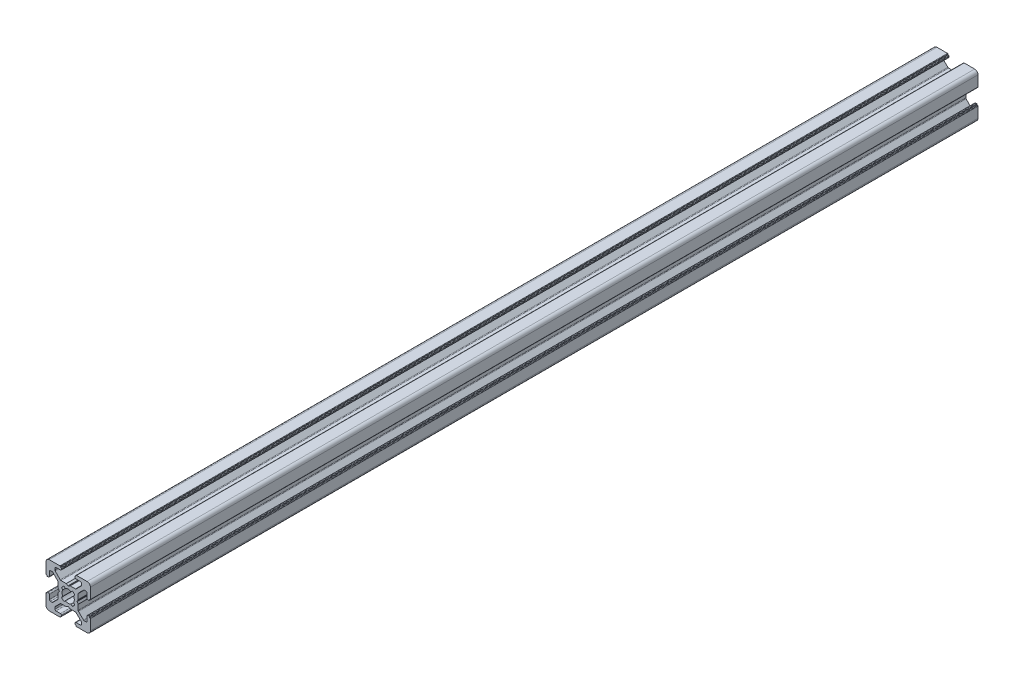
SolidWorks part; units mm, degrees
ref_plane "Front Plane" through (0, 0, 0) normal (0, 0, 1) x (1, 0, 0)
ref_plane "Top Plane" through (0, 0, 0) normal (0, 1, 0) x (1, 0, 0)
ref_plane "Right Plane" through (0, 0, 0) normal (1, 0, 0) x (0, 0, -1)
sketch "Sketch1" plane through (0, 0, 0) normal (0, 0, 1) x (1, 0, 0)
  line L0 (0, 13.3675) -> (0, -10.9159) construction
  line L1 (-12.9725, 0) -> (15.1887, 0) construction
  line L2 (-3.5, 8.5) -> (-5.5, 8.5)
  line L3 (-3.55, 9.7) -> (-3.55, 9.8)
  line L4 (-6, 7.2678) -> (-6, 8)
  line L5 (-7.2678, 6) -> (-8, 6)
  line L6 (-3.75, 10) -> (-8.5, 10)
  line L7 (-9.7, 3.55) -> (-9.8, 3.55)
  line L8 (-9.5, 3.2) -> (-9.5, 3.35)
  line L9 (-9, 3) -> (-9.3, 3)
  line L10 (-4.4732, 0.8536) -> (-4.0381, 0.1)
  line L11 (-4.5, 3.2322) -> (-4.5, 0.9536)
  line L12 (-8.5, 3.5) -> (-8.5, 5.5)
  line L13 (-10, 3.75) -> (-10, 8.5)
  line L14 (-3.5858, 4.6464) -> (-5.8536, 6.9142)
  line L15 (-4.6464, 3.5858) -> (-6.9142, 5.8536)
  line L16 (-3.2, 9.5) -> (-3.35, 9.5)
  line L17 (-3, 9) -> (-3, 9.3)
  line L18 (-0.8536, 4.4732) -> (-0.1, 4.0381)
  line L19 (-3.2322, 4.5) -> (-0.9536, 4.5)
  line L20 (-1.2582, 2.4453) -> (-1.9139, 2.9896)
  line L21 (-2.4453, 1.2582) -> (-2.9922, 1.9099)
  line L22 (3.5, -8.5) -> (5.5, -8.5)
  line L23 (3.55, -9.7) -> (3.55, -9.8)
  line L24 (6, -7.2678) -> (6, -8)
  line L25 (7.2678, -6) -> (8, -6)
  line L26 (3.75, -10) -> (8.5, -10)
  line L27 (9.7, -3.55) -> (9.8, -3.55)
  line L28 (9.5, -3.2) -> (9.5, -3.35)
  line L29 (9, -3) -> (9.3, -3)
  line L30 (4.4732, -0.8536) -> (4.0381, -0.1)
  line L31 (4.5, -3.2322) -> (4.5, -0.9536)
  line L32 (8.5, -3.5) -> (8.5, -5.5)
  line L33 (10, -3.75) -> (10, -8.5)
  line L34 (3.5858, -4.6464) -> (5.8536, -6.9142)
  line L35 (4.6464, -3.5858) -> (6.9142, -5.8536)
  line L36 (3.2, -9.5) -> (3.35, -9.5)
  line L37 (3, -9) -> (3, -9.3)
  line L38 (0.8536, -4.4732) -> (0.1, -4.0381)
  line L39 (3.2322, -4.5) -> (0.9536, -4.5)
  line L40 (1.2582, -2.4453) -> (1.9139, -2.9896)
  line L41 (2.4453, -1.2582) -> (2.9922, -1.9099)
  line L42 (-2.4453, -1.2582) -> (-2.9922, -1.9099)
  line L43 (-1.2582, -2.4453) -> (-1.9139, -2.9896)
  line L44 (-3.2322, -4.5) -> (-0.9536, -4.5)
  line L45 (-0.8536, -4.4732) -> (-0.1, -4.0381)
  line L46 (-3, -9) -> (-3, -9.3)
  line L47 (-3.2, -9.5) -> (-3.35, -9.5)
  line L48 (-4.6464, -3.5858) -> (-6.9142, -5.8536)
  line L49 (-3.5858, -4.6464) -> (-5.8536, -6.9142)
  line L50 (-10, -3.75) -> (-10, -8.5)
  line L51 (-8.5, -3.5) -> (-8.5, -5.5)
  line L52 (-4.5, -3.2322) -> (-4.5, -0.9536)
  line L53 (-4.4732, -0.8536) -> (-4.0381, -0.1)
  line L54 (-9, -3) -> (-9.3, -3)
  line L55 (-9.5, -3.2) -> (-9.5, -3.35)
  line L56 (-9.7, -3.55) -> (-9.8, -3.55)
  line L57 (2.4453, 1.2582) -> (2.9922, 1.9099)
  line L58 (1.2582, 2.4453) -> (1.9139, 2.9896)
  line L59 (3.2322, 4.5) -> (0.9536, 4.5)
  line L60 (0.8536, 4.4732) -> (0.1, 4.0381)
  line L61 (-3.75, -10) -> (-8.5, -10)
  line L62 (-7.2678, -6) -> (-8, -6)
  line L63 (-6, -7.2678) -> (-6, -8)
  line L64 (3, 9) -> (3, 9.3)
  line L65 (3.2, 9.5) -> (3.35, 9.5)
  line L66 (4.6464, 3.5858) -> (6.9142, 5.8536)
  line L67 (3.5858, 4.6464) -> (5.8536, 6.9142)
  line L68 (10, 3.75) -> (10, 8.5)
  line L69 (8.5, 3.5) -> (8.5, 5.5)
  line L70 (4.5, 3.2322) -> (4.5, 0.9536)
  line L71 (4.4732, 0.8536) -> (4.0381, 0.1)
  line L72 (9, 3) -> (9.3, 3)
  line L73 (9.5, 3.2) -> (9.5, 3.35)
  line L74 (9.7, 3.55) -> (9.8, 3.55)
  line L75 (3.75, 10) -> (8.5, 10)
  line L76 (7.2678, 6) -> (8, 6)
  line L77 (6, 7.2678) -> (6, 8)
  line L78 (3.55, 9.7) -> (3.55, 9.8)
  line L79 (3.5, 8.5) -> (5.5, 8.5)
  line L80 (-3.55, -9.7) -> (-3.55, -9.8)
  line L81 (-3.5, -8.5) -> (-5.5, -8.5)
  arc A0 (-10, 8.5) -> (-8.5, 10) centre (-8.5, 8.5) cw
  arc A1 (-8.5, 5.5) -> (-8, 6) centre (-8, 5.5) cw
  arc A2 (-7.2678, 6) -> (-6.9142, 5.8536) centre (-7.2678, 5.5) cw
  arc A3 (-5.8536, 6.9142) -> (-6, 7.2678) centre (-5.5, 7.2678) cw
  arc A4 (-6, 8) -> (-5.5, 8.5) centre (-5.5, 8) cw
  arc A5 (-9.7, 3.55) -> (-9.5, 3.35) centre (-9.7, 3.35) cw
  arc A6 (-9.8, 3.55) -> (-10, 3.75) centre (-9.8, 3.75) cw
  arc A7 (-9.3, 3) -> (-9.5, 3.2) centre (-9.3, 3.2) cw
  arc A8 (-8.5, 3.5) -> (-9, 3) centre (-9, 3.5) cw
  arc A9 (-4.6464, 3.5858) -> (-4.5, 3.2322) centre (-5, 3.2322) cw
  arc A10 (-4.4732, 0.8536) -> (-4.5, 0.9536) centre (-4.3, 0.9536) cw
  arc A11 (-4.0381, 0.1) -> (-4.0381, -0.1) centre (-4.2113, 0) cw
  arc A12 (-3.2, 9.5) -> (-3, 9.3) centre (-3.2, 9.3) cw
  arc A13 (-0.9536, 4.5) -> (-0.8536, 4.4732) centre (-0.9536, 4.3) cw
  arc A14 (-2.9922, 1.9099) -> (-1.9139, 2.9896) centre (0, 0) cw
  arc A15 (-3.2322, 4.5) -> (-3.5858, 4.6464) centre (-3.2322, 5) cw
  arc A16 (-3.75, 10) -> (-3.55, 9.8) centre (-3.75, 9.8) cw
  arc A17 (-3.35, 9.5) -> (-3.55, 9.7) centre (-3.35, 9.7) cw
  arc A18 (2.4453, -1.2582) -> (2.4453, 1.2582) centre (0, 0) ccw
  arc A19 (-3, 9) -> (-3.5, 8.5) centre (-3.5, 9) cw
  arc A20 (-2.4453, -1.2582) -> (-2.4453, 1.2582) centre (0, 0) cw
  arc A21 (10, -8.5) -> (8.5, -10) centre (8.5, -8.5) cw
  arc A22 (8.5, -5.5) -> (8, -6) centre (8, -5.5) cw
  arc A23 (7.2678, -6) -> (6.9142, -5.8536) centre (7.2678, -5.5) cw
  arc A24 (5.8536, -6.9142) -> (6, -7.2678) centre (5.5, -7.2678) cw
  arc A25 (6, -8) -> (5.5, -8.5) centre (5.5, -8) cw
  arc A26 (9.7, -3.55) -> (9.5, -3.35) centre (9.7, -3.35) cw
  arc A27 (9.8, -3.55) -> (10, -3.75) centre (9.8, -3.75) cw
  arc A28 (9.3, -3) -> (9.5, -3.2) centre (9.3, -3.2) cw
  arc A29 (8.5, -3.5) -> (9, -3) centre (9, -3.5) cw
  arc A30 (4.6464, -3.5858) -> (4.5, -3.2322) centre (5, -3.2322) cw
  arc A31 (4.4732, -0.8536) -> (4.5, -0.9536) centre (4.3, -0.9536) cw
  arc A32 (3.2, -9.5) -> (3, -9.3) centre (3.2, -9.3) cw
  arc A33 (-0.1, -4.0381) -> (0.1, -4.0381) centre (0, -4.2113) cw
  arc A34 (0.9536, -4.5) -> (0.8536, -4.4732) centre (0.9536, -4.3) cw
  arc A35 (2.9922, -1.9099) -> (1.9139, -2.9896) centre (0, 0) cw
  arc A36 (1.2582, -2.4453) -> (-1.2582, -2.4453) centre (0, 0) cw
  arc A37 (3.2322, -4.5) -> (3.5858, -4.6464) centre (3.2322, -5) cw
  arc A38 (3.75, -10) -> (3.55, -9.8) centre (3.75, -9.8) cw
  arc A39 (3.35, -9.5) -> (3.55, -9.7) centre (3.35, -9.7) cw
  arc A40 (3, -9) -> (3.5, -8.5) centre (3.5, -9) cw
  arc A41 (-3, -9) -> (-3.5, -8.5) centre (-3.5, -9) ccw
  arc A42 (-3.35, -9.5) -> (-3.55, -9.7) centre (-3.35, -9.7) ccw
  arc A43 (-3.75, -10) -> (-3.55, -9.8) centre (-3.75, -9.8) ccw
  arc A44 (-3.2322, -4.5) -> (-3.5858, -4.6464) centre (-3.2322, -5) ccw
  arc A45 (-2.9922, -1.9099) -> (-1.9139, -2.9896) centre (0, 0) ccw
  arc A46 (-0.9536, -4.5) -> (-0.8536, -4.4732) centre (-0.9536, -4.3) ccw
  arc A47 (-3.2, -9.5) -> (-3, -9.3) centre (-3.2, -9.3) ccw
  arc A48 (-4.4732, -0.8536) -> (-4.5, -0.9536) centre (-4.3, -0.9536) ccw
  arc A49 (3, 9) -> (3.5, 8.5) centre (3.5, 9) ccw
  arc A50 (3.35, 9.5) -> (3.55, 9.7) centre (3.35, 9.7) ccw
  arc A51 (3.75, 10) -> (3.55, 9.8) centre (3.75, 9.8) ccw
  arc A52 (3.2322, 4.5) -> (3.5858, 4.6464) centre (3.2322, 5) ccw
  arc A53 (1.2582, 2.4453) -> (-1.2582, 2.4453) centre (0, 0) ccw
  arc A54 (-4.6464, -3.5858) -> (-4.5, -3.2322) centre (-5, -3.2322) ccw
  arc A55 (-8.5, -3.5) -> (-9, -3) centre (-9, -3.5) ccw
  arc A56 (-9.3, -3) -> (-9.5, -3.2) centre (-9.3, -3.2) ccw
  arc A57 (-9.8, -3.55) -> (-10, -3.75) centre (-9.8, -3.75) ccw
  arc A58 (-9.7, -3.55) -> (-9.5, -3.35) centre (-9.7, -3.35) ccw
  arc A59 (-6, -8) -> (-5.5, -8.5) centre (-5.5, -8) ccw
  arc A60 (2.9922, 1.9099) -> (1.9139, 2.9896) centre (0, 0) ccw
  arc A61 (0.9536, 4.5) -> (0.8536, 4.4732) centre (0.9536, 4.3) ccw
  arc A62 (-0.1, 4.0381) -> (0.1, 4.0381) centre (0, 4.2113) ccw
  arc A63 (-5.8536, -6.9142) -> (-6, -7.2678) centre (-5.5, -7.2678) ccw
  arc A64 (-7.2678, -6) -> (-6.9142, -5.8536) centre (-7.2678, -5.5) ccw
  arc A65 (-8.5, -5.5) -> (-8, -6) centre (-8, -5.5) ccw
  arc A66 (-10, -8.5) -> (-8.5, -10) centre (-8.5, -8.5) ccw
  arc A67 (3.2, 9.5) -> (3, 9.3) centre (3.2, 9.3) ccw
  arc A68 (4.0381, 0.1) -> (4.0381, -0.1) centre (4.2113, 0) ccw
  arc A69 (4.4732, 0.8536) -> (4.5, 0.9536) centre (4.3, 0.9536) ccw
  arc A70 (4.6464, 3.5858) -> (4.5, 3.2322) centre (5, 3.2322) ccw
  arc A71 (8.5, 3.5) -> (9, 3) centre (9, 3.5) ccw
  arc A72 (9.3, 3) -> (9.5, 3.2) centre (9.3, 3.2) ccw
  arc A73 (9.8, 3.55) -> (10, 3.75) centre (9.8, 3.75) ccw
  arc A74 (9.7, 3.55) -> (9.5, 3.35) centre (9.7, 3.35) ccw
  arc A75 (6, 8) -> (5.5, 8.5) centre (5.5, 8) ccw
  arc A76 (5.8536, 6.9142) -> (6, 7.2678) centre (5.5, 7.2678) ccw
  arc A77 (7.2678, 6) -> (6.9142, 5.8536) centre (7.2678, 5.5) ccw
  arc A78 (8.5, 5.5) -> (8, 6) centre (8, 5.5) ccw
  arc A79 (10, 8.5) -> (8.5, 10) centre (8.5, 8.5) ccw
  dimension "D4" = 5.5
  dimension "D1" = 6
  dimension "D2" = 20
  dimension "D3" = 20
  dimension "D5" = 5.5
  dimension "D6" = 10
  dimension "D7" = 6
  dimension "D8" = 6
  dimension "D9" = 6
extrude "Extrude1" add sketch "Sketch1" along normal blind 400
